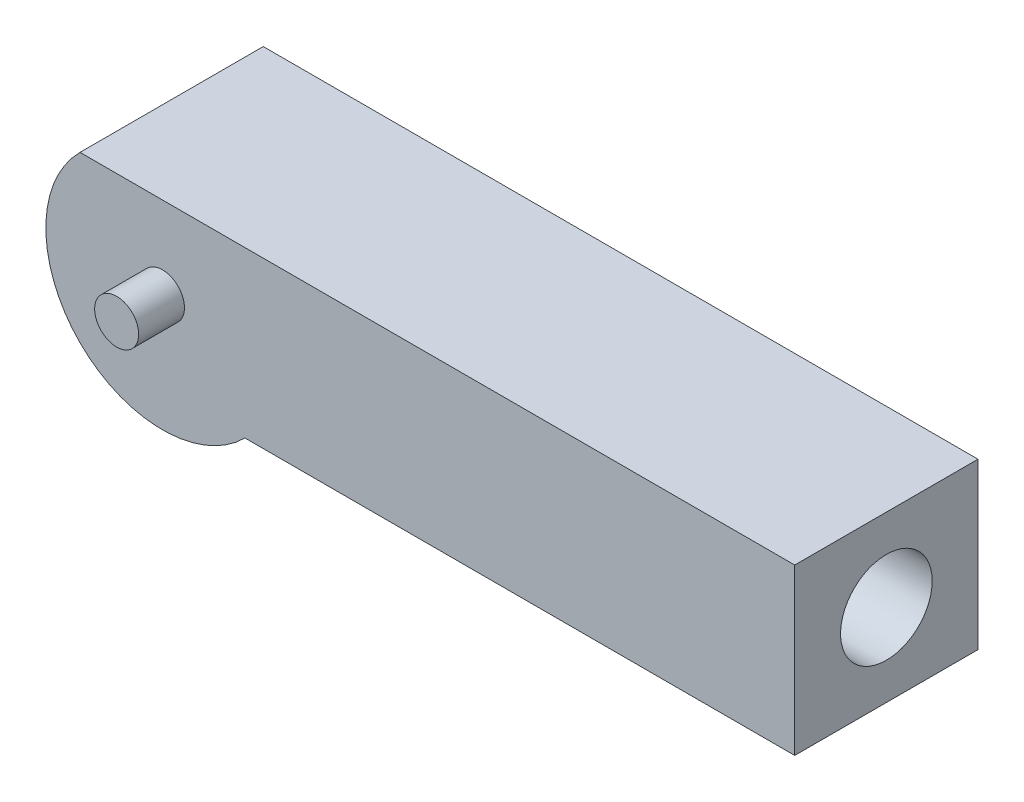
SolidWorks part; units mm, degrees
ref_plane "Front Plane" through (0, 0, 0) normal (0, 0, 1) x (1, 0, 0)
ref_plane "Top Plane" through (0, 0, 0) normal (0, 1, 0) x (1, 0, 0)
ref_plane "Right Plane" through (0, 0, 0) normal (1, 0, 0) x (0, 0, -1)
sketch "Sketch1" plane through (0, 0, 0) normal (0, 0, 1) x (1, 0, 0)
  line L0 (5.715, -5.715) -> (43.815, -5.715)
  line L1 (-5.715, -5.715) -> (5.715, -5.715) construction
  line L2 (-5.715, -5.715) -> (-5.715, 5.715) construction
  line L3 (-5.715, 5.715) -> (5.715, 5.715)
  line L4 (5.715, -5.715) -> (5.715, 5.715) construction
  line L5 (-5.715, -5.715) -> (5.715, 5.715) construction
  line L6 (-5.715, 5.715) -> (5.715, -5.715) construction
  line L7 (43.815, -5.715) -> (43.815, 5.715)
  line L8 (43.815, 5.715) -> (5.715, 5.715)
  arc A0 (-5.715, 5.715) -> (5.715, -5.715) centre (0, 0) ccw
  point P0 (0, 0)
  dimension "D3" = 38.1
  dimension "D1" = 11.43
  dimension "D2" = 11.43
extrude "Boss-Extrude1" add sketch "Sketch1" along normal blind 12.7
sketch "Sketch3" plane through (0, 0, 12.7) normal (0, 0, 1) x (1, 0, 0)
  line L0 (5.715, -5.715) -> (-5.715, 5.715) construction
  circle A0 centre (0, 0) radius 1.524
  dimension "D1" = 3.048
extrude "Boss-Extrude2" add sketch "Sketch3" along normal blind 3.175 and the other way blind 15.875
sketch "Sketch2" plane through (43.815, 0, 0) normal (1, 0, 0) x (0, 0, -1)
  line L0 (-12.7, 5.715) -> (0, -5.715) construction
  line L4 (0, -5.715) -> (0, 5.715)
  line L5 (0, 5.715) -> (-12.7, 5.715)
  line L6 (-12.7, 5.715) -> (-12.7, -5.715)
  line L7 (-12.7, -5.715) -> (0, -5.715)
  line L8 (0, -5.715) -> (0, 5.715) construction
  line L9 (0, 5.715) -> (-12.7, 5.715) construction
  line L10 (-12.7, 5.715) -> (-12.7, -5.715) construction
  line L11 (-12.7, -5.715) -> (0, -5.715) construction
  circle A0 centre (-6.35, 0) radius 3.175
  dimension "D2" = 6.35
  dimension "D1" = 0
extrude "Cut-Extrude1" cut sketch "Sketch2" against normal through all contours A0
